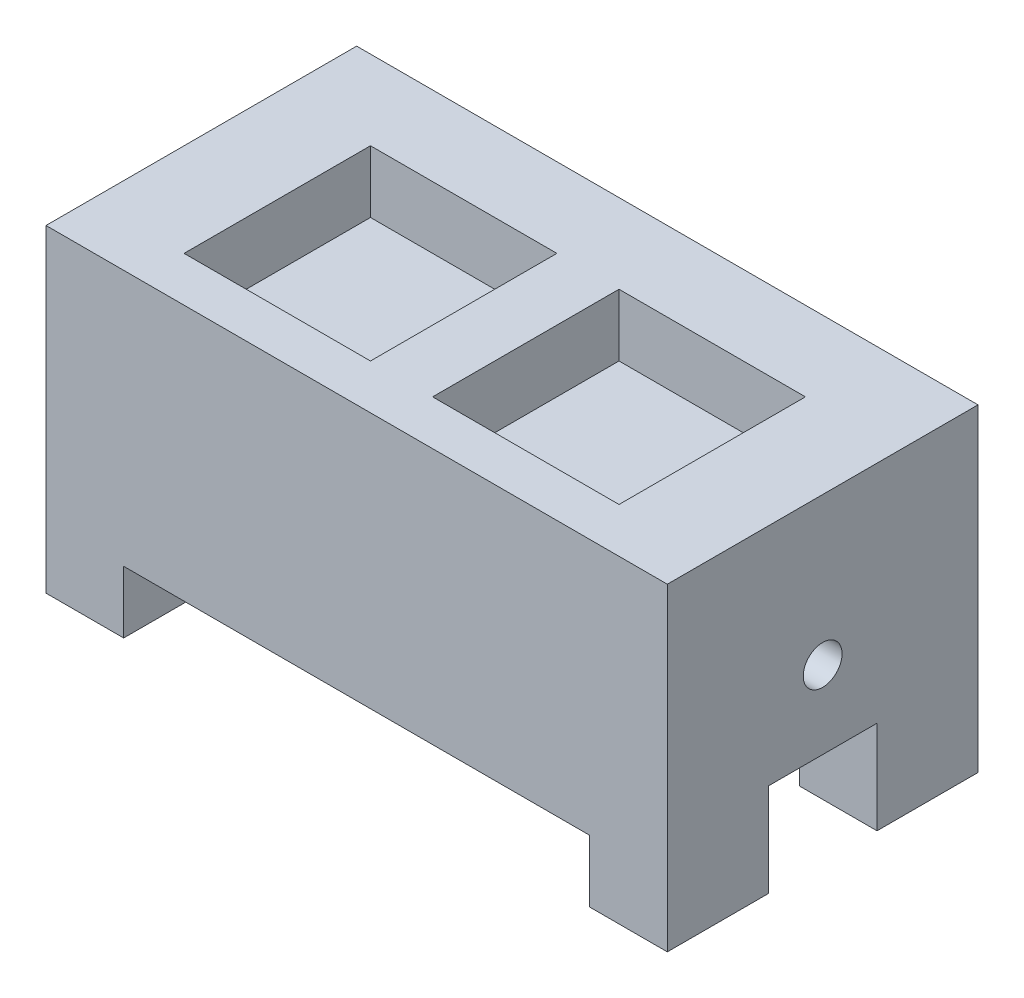
SolidWorks part; units mm, degrees
ref_plane "Спереди" through (0, 0, 0) normal (0, 0, 1) x (1, 0, 0)
ref_plane "Сверху" through (0, 0, 0) normal (0, 1, 0) x (1, 0, 0)
ref_plane "Справа" through (0, 0, 0) normal (1, 0, 0) x (0, 0, -1)
sketch "Эскиз1" plane through (0, 0, 0) normal (0, 0, 1) x (1, 0, 0)
  line L0 (0, 0) -> (10, 0)
  line L1 (10, 0) -> (10, 8)
  line L2 (10, 8) -> (70, 8)
  line L3 (70, 8) -> (70, 0)
  line L4 (70, 0) -> (80, 0)
  line L5 (80, 0) -> (80, 41)
  line L6 (80, 41) -> (0, 41)
  line L7 (0, 41) -> (0, 0)
  line L8 (-60.5707, 0) -> (60.6151, 0) construction
  dimension "D1" = 60
  dimension "D2" = 80
  dimension "D3" = 10
  dimension "D4" = 41
  dimension "D5" = 8
extrude "Бобышка-Вытянуть1" add sketch "Эскиз1" along normal blind 40 contours L7 L0 L1 L2 L3 L4 L5 L6
sketch "Эскиз2" plane through (0, 0, 0) normal (-1, 0, 0) x (0, 0, 1)
  line L0 (40, 0) -> (0, 0) construction
  line L1 (13, 0) -> (27, 0)
  line L2 (13, 0) -> (13, 12)
  line L3 (13, 12) -> (27, 12)
  line L4 (27, 0) -> (27, 12)
  line L5 (0, 41) -> (0, 0) construction
  line L7 (20, 12) -> (20, 28.7362) construction
  circle A0 centre (20, 22) radius 2.5
  point P12 (0, 0)
  dimension "D1" = 5
  dimension "D2" = 12
  dimension "D3" = 14
  dimension "D4" = 13
  dimension "D5" = 22
extrude "Вырез-Вытянуть1" cut sketch "Эскиз2" against normal through all contours A0 | L2 L1 L4 L3
sketch "Эскиз3" plane through (0, 41, 0) normal (0, 1, 0) x (1, 0, 0)
  line L0 (80, -40) -> (80, 0) construction
  line L1 (12, -10.2209) -> (36, -10.2209)
  line L2 (12, -10.2209) -> (12, -34.2209)
  line L3 (12, -34.2209) -> (36, -34.2209)
  line L4 (36, -10.2209) -> (36, -34.2209)
  line L5 (44, -10.2209) -> (68, -10.2209)
  line L6 (44, -10.2209) -> (44, -34.2209)
  line L7 (44, -34.2209) -> (68, -34.2209)
  line L8 (68, -10.2209) -> (68, -34.2209)
  dimension "D1" = 24
  dimension "D2" = 24
  dimension "D3" = 8
  dimension "D4" = 12
  dimension "D5" = 24
  dimension "D6" = 24
extrude "Вырез-Вытянуть2" cut sketch "Эскиз3" against normal blind 8
